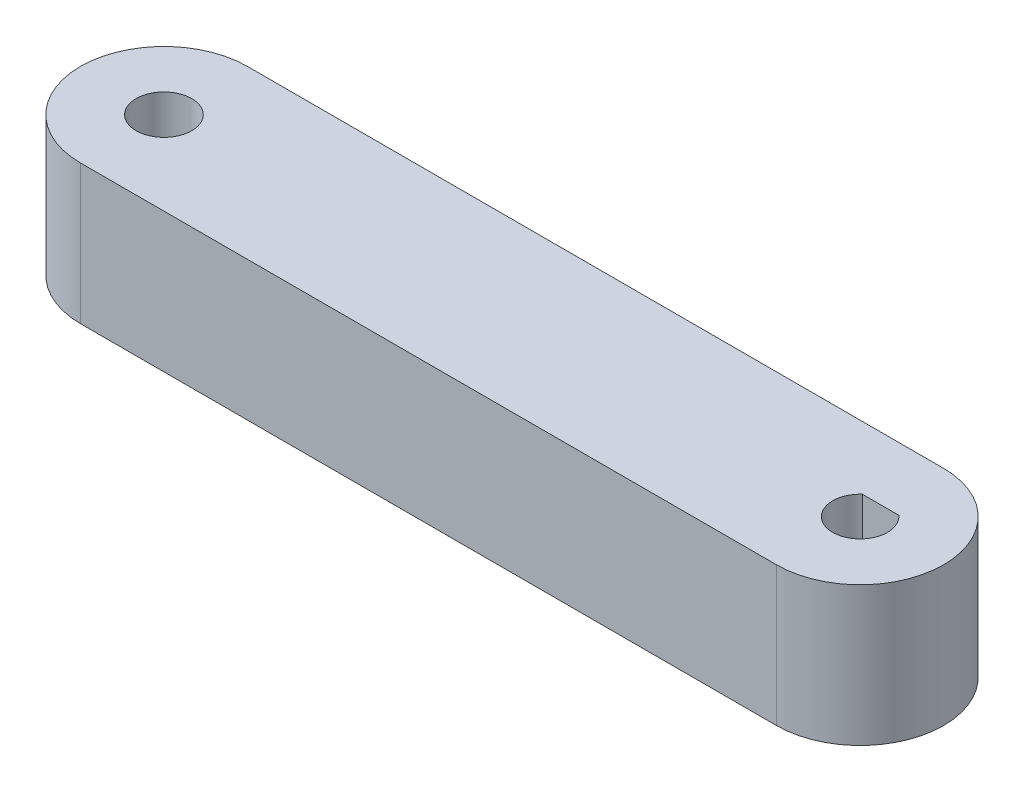
SolidWorks part; units mm, degrees
ref_plane "Front Plane" through (0, 0, 0) normal (0, 0, 1) x (1, 0, 0)
ref_plane "Top Plane" through (0, 0, 0) normal (0, 1, 0) x (1, 0, 0)
ref_plane "Right Plane" through (0, 0, 0) normal (1, 0, 0) x (0, 0, -1)
sketch "Sketch3" plane through (0, 0, 0) normal (0, 1, 0) x (1, 0, 0)
  line L0 (-31.75, 0) -> (31.75, 0) construction
  line L1 (-6.985, 0) -> (6.985, 0) construction
  line L2 (-31.75, 7.62) -> (31.75, 7.62)
  line L3 (-31.75, -7.62) -> (31.75, -7.62)
  arc A0 (-31.75, 7.62) -> (-31.75, -7.62) centre (-31.75, 0) ccw
  arc A1 (31.75, -7.62) -> (31.75, 7.62) centre (31.75, 0) ccw
  point P5 (0, 0)
  point P10 (0, 0)
  dimension "D2" = 7.62
  dimension "D1" = 63.5
  dimension "D3" = 31.75
extrude "Boss-Extrude1" add sketch "Sketch3" along normal blind 12.7
sketch "Sketch4" plane through (0, 12.7, 0) normal (0, 1, 0) x (1, 0, 0)
  circle A0 centre (-31.75, 0) radius 2.54
  dimension "D1" = 5.08
extrude "Cut-Extrude3" cut sketch "Sketch4" against normal through all
sketch "Sketch6" plane through (0, 12.7, 0) normal (0, 1, 0) x (1, 0, 0)
  line L0 (30.0912, 1.8704) -> (33.4088, 1.8704)
  circle A0 centre (31.75, 0) radius 2.5
  arc A1 (33.4088, 1.8704) -> (30.0912, 1.8704) centre (31.75, 0) ccw
  dimension "D1" = 5
  dimension "D2" = 1.8704
extrude "Cut-Extrude4" cut sketch "Sketch6" against normal through all contours L0 A0
equation "\"TibiaLength\"= 5in"
equation "\"TibiaRadius\"= 0.3in"
equation "\"TibiaDistFromCentre\"= \"TibiaLength\" / 2"
equation "\"TibiaThickness\"= 0.5in"
equation "\"HoleRadius\"= 0.2in"
equation "\"D1@Sketch3\"= \"TibiaLength\" * 0.5"
equation "\"D2@Sketch3\"= \"TibiaRadius\""
equation "\"D3@Sketch3\"=\"TibiaDistFromCentre\"/2"
equation "\"D1@Boss-Extrude1\"= \"TibiaThickness\""
equation "\"D1@Sketch4\"= \"HoleRadius\""
